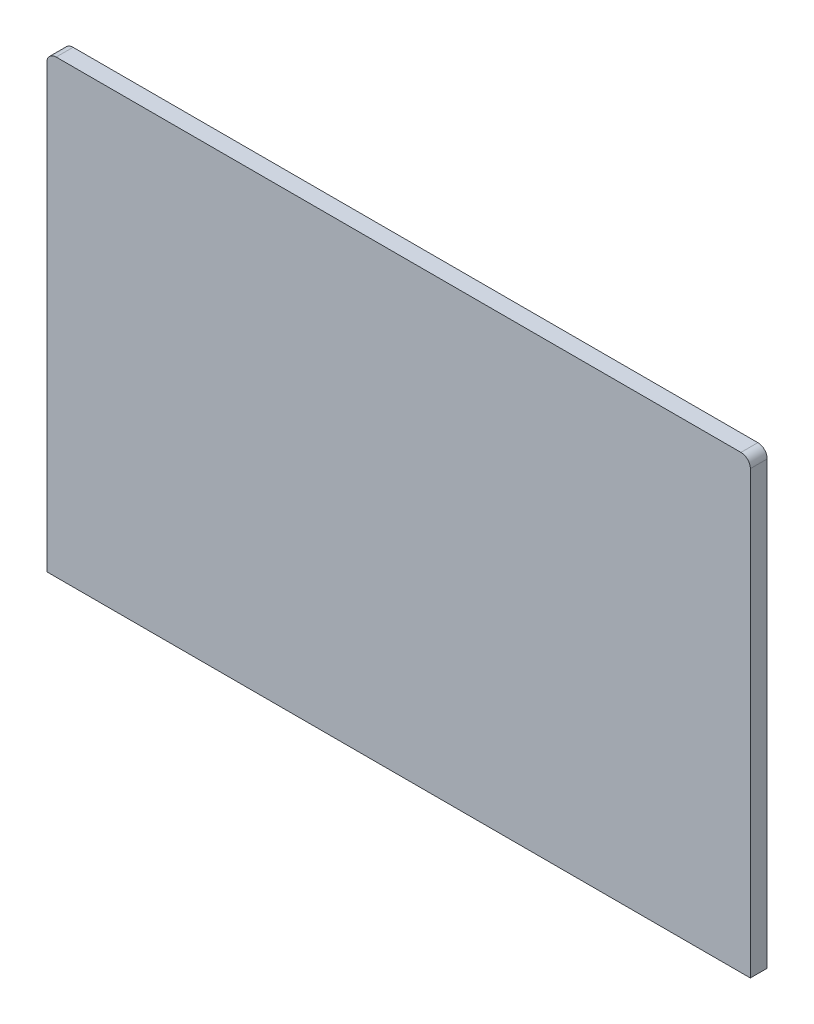
SolidWorks part; units mm, degrees
ref_plane "Plan de face" through (0, 0, 0) normal (0, 0, 1) x (1, 0, 0)
ref_plane "Plan de dessus" through (0, 0, 0) normal (0, 1, 0) x (1, 0, 0)
ref_plane "Plan de droite" through (0, 0, 0) normal (1, 0, 0) x (0, 0, -1)
sketch "Esquisse1" plane through (0, 0, 0) normal (0, 0, 1) x (1, 0, 0)
  line L1 (37.475, 23.995) -> (-37.475, 23.995)
  line L2 (37.475, 23.995) -> (37.475, -23.995)
  line L3 (37.475, -23.995) -> (-37.475, -23.995)
  line L4 (-37.475, 23.995) -> (-37.475, -23.995)
  line L5 (37.475, 23.995) -> (-37.475, -23.995) construction
  line L6 (37.475, -23.995) -> (-37.475, 23.995) construction
  point P0 (0, 0)
extrude "Boss.-Extru.1" add sketch "Esquisse1" along normal blind 1.8
fillet "Congé1" radius 1 2 edges at (-37.475, 23.995, 0.9) (37.475, 23.995, 0.9)
